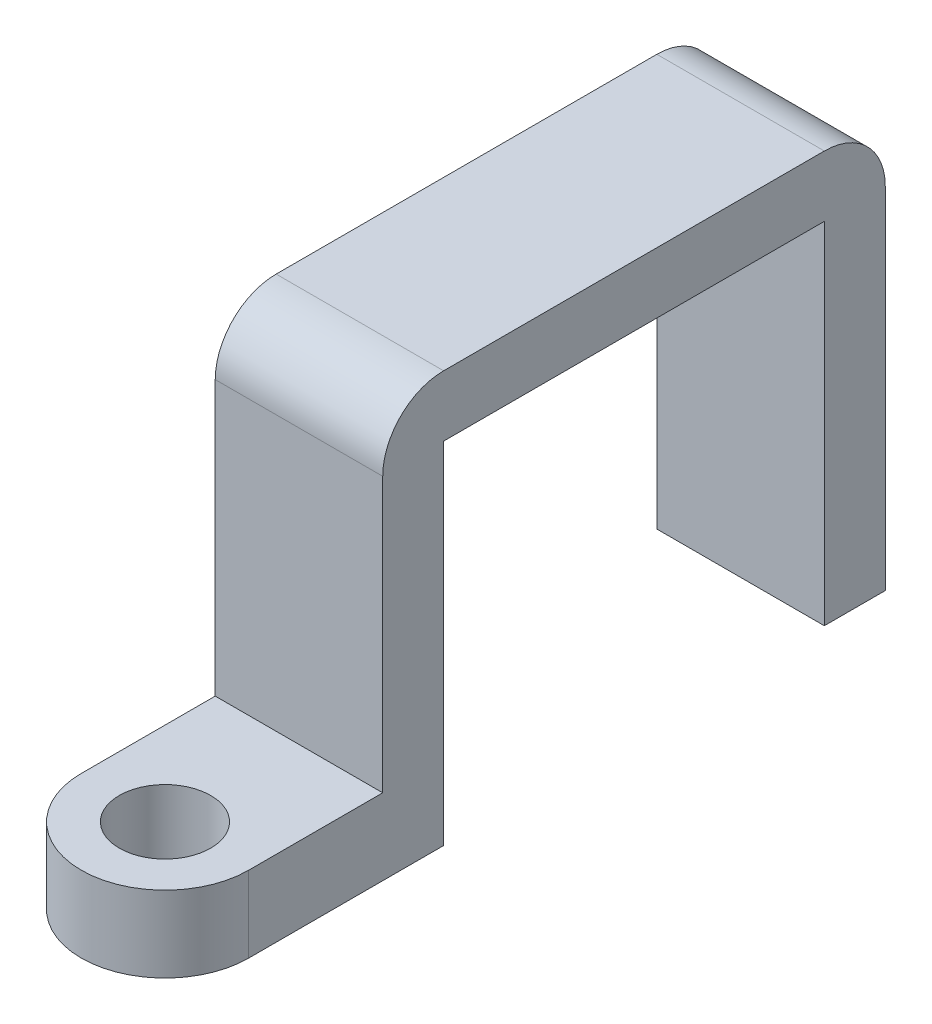
SolidWorks part; units mm, degrees
ref_plane "Front Plane" through (0, 0, 0) normal (0, 0, 1) x (1, 0, 0)
ref_plane "Top Plane" through (0, 0, 0) normal (0, 1, 0) x (1, 0, 0)
ref_plane "Right Plane" through (0, 0, 0) normal (1, 0, 0) x (0, 0, -1)
sketch "Sketch2" plane through (0, 0, 0) normal (0, 1, 0) x (1, 0, 0)
  line L0 (0, 0) -> (0, 6.4) construction
  line L1 (-2.75, 0) -> (-2.75, 6.4)
  line L2 (2.75, 0) -> (2.75, 6.4)
  line L3 (-2.75, 6.4) -> (2.75, 6.4)
  arc A0 (-2.75, 0) -> (2.75, 0) centre (0, 0) ccw
  circle A1 centre (0, 0) radius 1.5
  dimension "D1" = 5.5
  dimension "D2" = 3
extrude "Boss-Extrude1" add sketch "Sketch2" along normal blind 2.5
sketch "Sketch3" plane through (0, 2.5, 0) normal (0, 1, 0) x (1, 0, 0)
  line L0 (-2.75, 6.4) -> (-2.75, 4.4)
  line L1 (-2.75, 6.4) -> (-2.75, 0) construction
  line L2 (-2.75, 4.4) -> (2.75, 4.4)
  line L3 (2.75, 0) -> (2.75, 6.4) construction
  line L4 (2.75, 4.4) -> (2.75, 6.4)
  line L5 (2.75, 6.4) -> (-2.75, 6.4)
extrude "Boss-Extrude2" add sketch "Sketch3" along normal blind 9
sketch "Sketch4" plane through (0, 11.5, 0) normal (0, 1, 0) x (1, 0, 0)
  line L0 (2.75, 20.9) -> (2.75, 4.4)
  line L1 (-2.75, 4.4) -> (2.75, 4.4)
  line L3 (2.75, 20.9) -> (-2.75, 20.9)
  line L4 (-2.75, 20.9) -> (-2.75, 4.4)
  dimension "D1" = 16.5
extrude "Boss-Extrude3" add sketch "Sketch4" along normal blind 2
sketch "Sketch5" plane through (0, 11.5, 0) normal (0, -1, 0) x (1, 0, 0)
  line L0 (2.75, -6.4) -> (2.75, -20.9) construction
  line L1 (-2.75, -20.9) -> (2.75, -20.9)
  line L2 (-2.75, -20.9) -> (-2.75, -18.9)
  line L3 (-2.75, -18.9) -> (2.75, -18.9)
  line L4 (2.75, -20.9) -> (2.75, -18.9)
  dimension "D1" = 2
extrude "Boss-Extrude4" add sketch "Sketch5" along normal blind 11.5
fillet "Fillet1" radius 2 2 edges at (0, 13.5, -4.4) (0, 13.5, -20.9)
